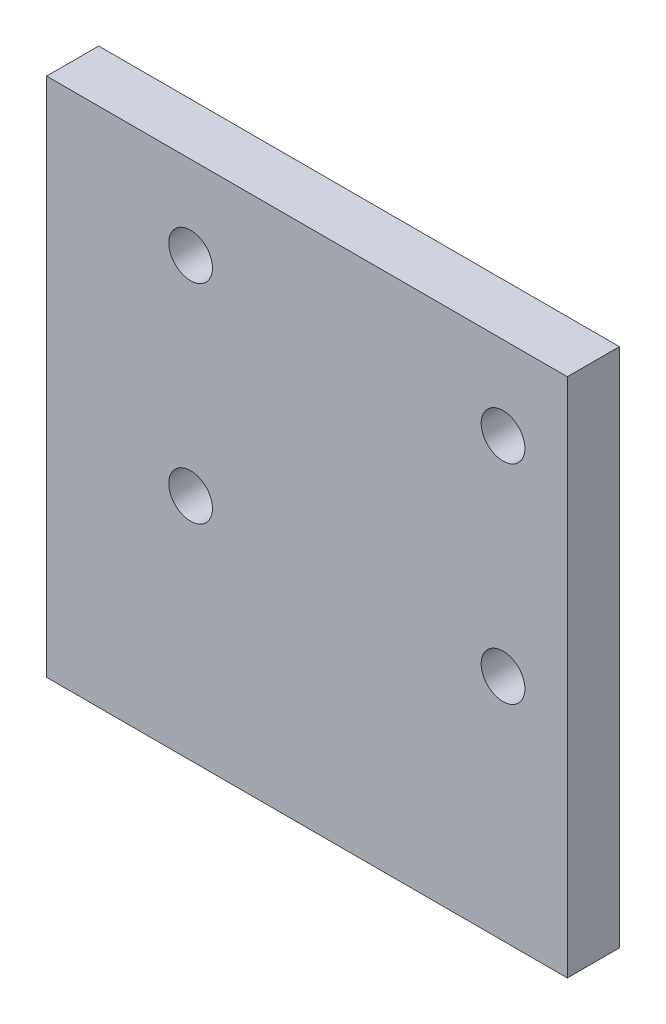
SolidWorks part; units mm, degrees
ref_plane "정면" through (0, 0, 0) normal (0, 0, 1) x (1, 0, 0)
ref_plane "윗면" through (0, 0, 0) normal (0, 1, 0) x (1, 0, 0)
ref_plane "우측면" through (0, 0, 0) normal (1, 0, 0) x (0, 0, -1)
sketch "스케치1" plane through (0, 0, 0) normal (0, 0, 1) x (1, 0, 0)
  line L1 (-25, 25) -> (25, 25)
  line L2 (-25, 25) -> (-25, -25)
  line L3 (-25, -25) -> (25, -25)
  line L4 (25, 25) -> (25, -25)
  line L5 (-25, 25) -> (25, -25) construction
  line L6 (-25, -25) -> (25, 25) construction
  point P0 (0, 0)
  dimension "D1" = 50
  dimension "D2" = 50
extrude "보스-돌출1" add sketch "스케치1" along normal blind 5
sketch "스케치2" plane through (0, 0, 5) normal (0, 0, 1) x (1, 0, 0)
  line L0 (-25, -25) -> (25, -25) construction
  circle A0 centre (-11.1735, -3) radius 2.1
  circle A1 centre (18.8265, -3) radius 2.1
  circle A2 centre (-11.1735, 17) radius 2.1
  circle A3 centre (18.8265, 17) radius 2.1
  point P10 (0, 0)
  point P11 (0, 0)
  dimension "D7" = 4.2
  dimension "D8" = 4.2
  dimension "D9" = 4.2
  dimension "D10" = 4.2
  dimension "D1" = 22
  dimension "D2" = 20
  dimension "D3" = 22
  dimension "D4" = 20
  dimension "D5" = 30
  dimension "D6" = 30
extrude "컷-돌출1" cut sketch "스케치2" against normal blind 5
